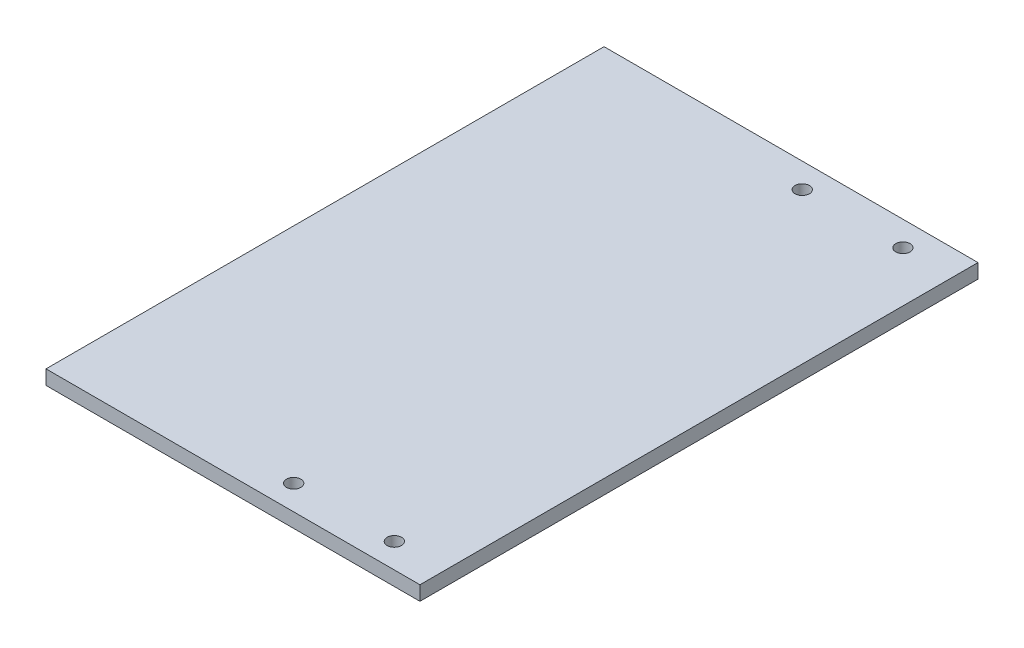
SolidWorks part; units mm, degrees
ref_plane "Front Plane" through (0, 0, 0) normal (0, 0, 1) x (1, 0, 0)
ref_plane "Top Plane" through (0, 0, 0) normal (0, 1, 0) x (1, 0, 0)
ref_plane "Right Plane" through (0, 0, 0) normal (1, 0, 0) x (0, 0, -1)
sketch "Sketch1" plane through (0, 0, 0) normal (0, 1, 0) x (1, 0, 0)
  line L0 (95, -3.772) -> (95, -11.5116) construction
  line L1 (0, 0) -> (130, 0)
  line L3 (0, -194) -> (130, -194)
  line L5 (0, 0) -> (0, -194)
  line L9 (130, 0) -> (130, -194)
  line L10 (52.0928, -97) -> (71.7794, -97) construction
  circle A0 centre (77.5, -8.5992) radius 2.5
  circle A1 centre (112.5, -8.5992) radius 2.5
  circle A2 centre (112.5, -185.4008) radius 2.5
  circle A3 centre (77.5, -185.4008) radius 2.5
  dimension "D1" = 194
  dimension "D2" = 130
extrude "Boss-Extrude1" add sketch "Sketch1" along normal blind 5
